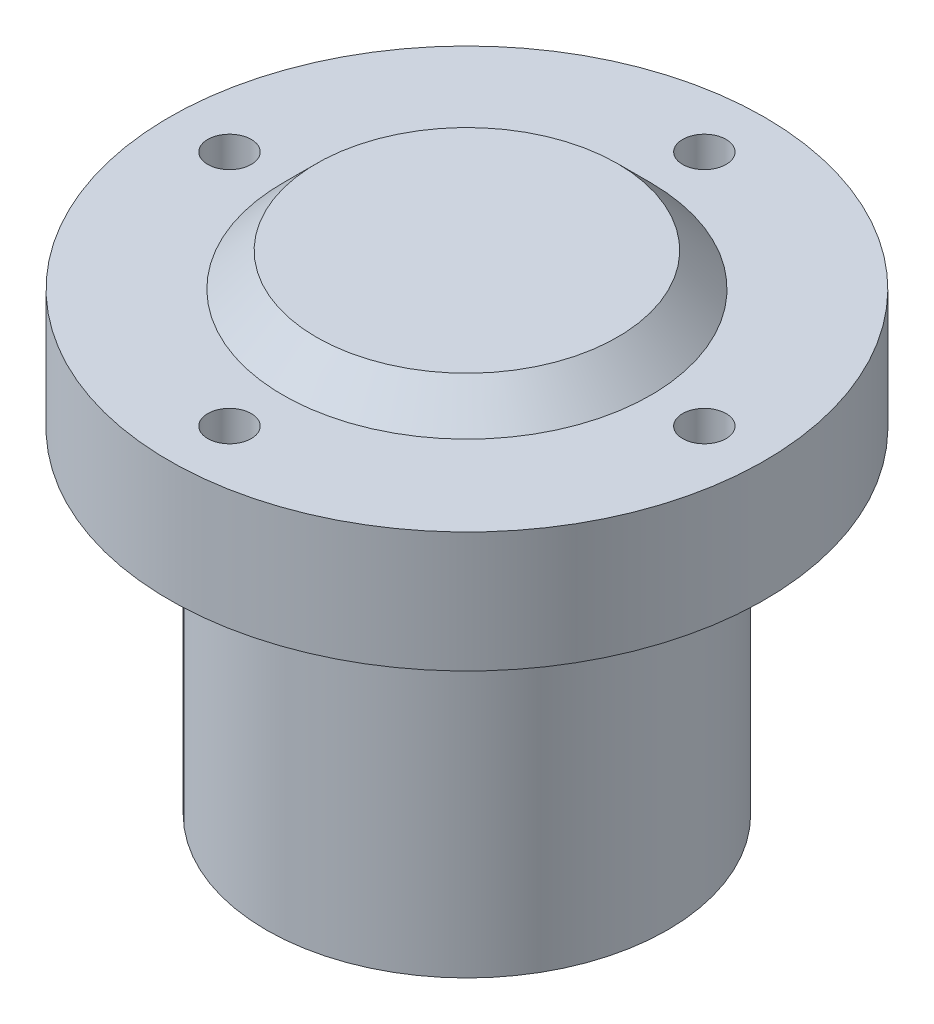
SolidWorks part; units mm, degrees
ref_plane "Front Plane" through (0, 0, 0) normal (0, 0, 1) x (1, 0, 0)
ref_plane "Top Plane" through (0, 0, 0) normal (0, 1, 0) x (1, 0, 0)
ref_plane "Right Plane" through (0, 0, 0) normal (1, 0, 0) x (0, 0, -1)
sketch "Sketch1" plane through (0, 0, 0) normal (0, 0, 1) x (1, 0, 0)
  line L0 (0, 0) -> (0, 161.6317) construction
  line L1 (0, 73) -> (22.5, 73)
  line L2 (22.5, 73) -> (27.5, 68)
  line L3 (27.5, 68) -> (44.5, 68)
  line L4 (44.5, 68) -> (44.5, 50)
  line L5 (44.5, 50) -> (30, 50)
  line L6 (30, 50) -> (30, 0)
  line L7 (30, 0) -> (0, 0)
  line L8 (0, 0) -> (0, 73)
  dimension "D1" = 89
  dimension "D2" = 60
  dimension "D3" = 18
  dimension "D4" = 50
  dimension "D5" = 45
  dimension "D6" = 5
  dimension "D7" = 45
revolve "Revolve1" add sketch "Sketch1" angle 360 about L0
sketch "Sketch2" plane through (0, 68, 0) normal (0, 1, 0) x (1, 0, 0)
  circle A0 centre (0, 0) radius 35.5 construction
  circle A1 centre (0, 35.5) radius 3.25
  circle A2 centre (35.5, 0) radius 3.25
  circle A3 centre (0, -35.5) radius 3.25
  circle A4 centre (-35.5, 0) radius 3.25
  dimension "D1" = 71
  dimension "D2" = 6.5
extrude "Cut-Extrude1" cut sketch "Sketch2" against normal blind 30
